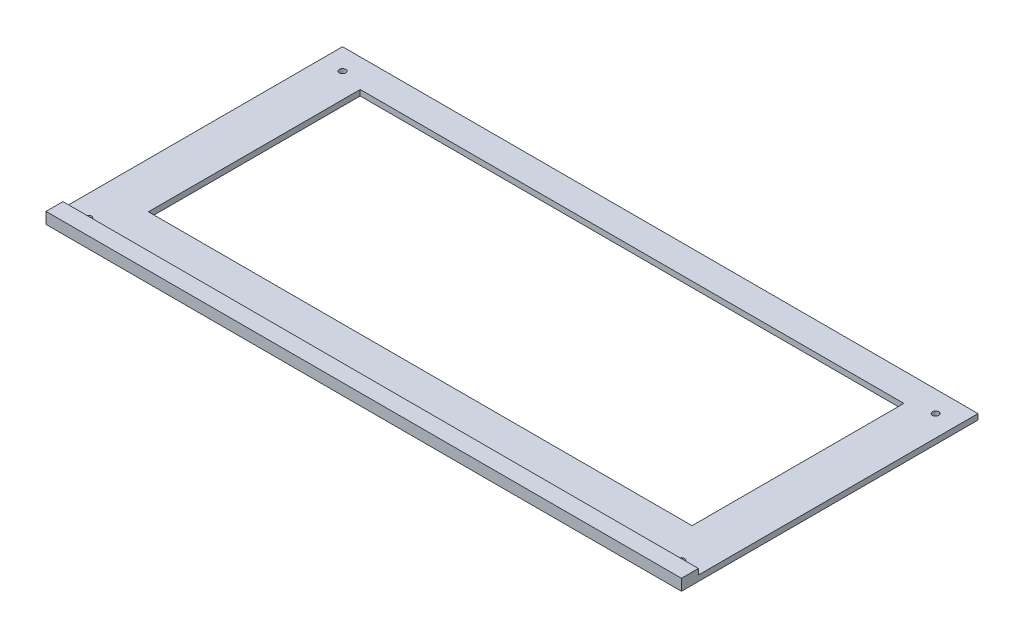
SolidWorks part; units mm, degrees
ref_plane "前视基准面" through (0, 0, 0) normal (0, 0, 1) x (1, 0, 0)
ref_plane "上视基准面" through (0, 0, 0) normal (0, 1, 0) x (1, 0, 0)
ref_plane "右视基准面" through (0, 0, 0) normal (1, 0, 0) x (0, 0, -1)
other "Configuration Table"
sketch "01_Guard_Outline" plane through (0, 0, 0) normal (0, 1, 0) x (1, 0, 0)
  line L1 (-450, -210) -> (450, -210)
  line L2 (-450, -210) -> (-450, 210)
  line L3 (-450, 210) -> (450, 210)
  line L4 (450, -210) -> (450, 210)
  line L5 (-450, -210) -> (450, 210) construction
  line L6 (-450, 210) -> (450, -210) construction
  line L7 (-385, -130) -> (385, -130)
  line L8 (-385, -130) -> (-385, 170)
  line L9 (-385, 170) -> (385, 170)
  line L10 (385, -130) -> (385, 170)
  line L11 (-385, -130) -> (385, 170) construction
  line L12 (-385, 170) -> (385, -130) construction
  circle A0 centre (-420, -180) radius 4.5
  circle A1 centre (420, -180) radius 4.5
  circle A2 centre (-420, 180) radius 4.5
  circle A3 centre (420, 180) radius 4.5
  point P0 (0, 0)
  point P6 (0, 20)
extrude "01_Guard_Panel" add sketch "01_Guard_Outline" along normal blind 8
sketch "02_Frame_Rail_Profile" plane through (0, 0, 0) normal (0, 1, 0) x (1, 0, 0)
  line L0 (450, -210) -> (450, 210) construction
  line L1 (-450, -210) -> (450, -210)
  line L2 (-450, -210) -> (-450, -186)
  line L3 (-450, -186) -> (450, -186)
  line L4 (450, -210) -> (450, -186)
  line L5 (-450, -210) -> (450, -186) construction
  line L6 (-450, -186) -> (450, -210) construction
  point P0 (0, -198)
extrude "02_Frame_Rail" add sketch "02_Frame_Rail_Profile" along normal blind 16
